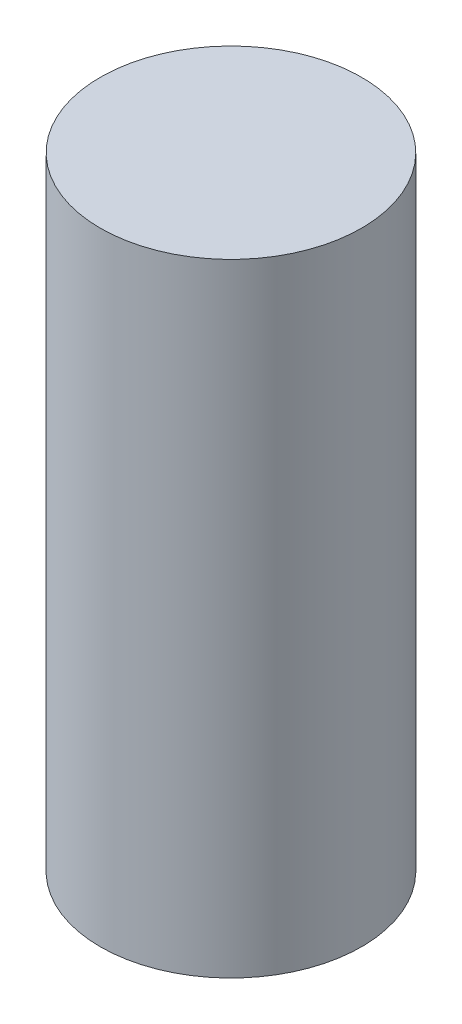
SolidWorks part; units mm, degrees
ref_plane "Plan de face" through (0, 0, 0) normal (0, 0, 1) x (1, 0, 0)
ref_plane "Plan de dessus" through (0, 0, 0) normal (0, 1, 0) x (1, 0, 0)
ref_plane "Plan de droite" through (0, 0, 0) normal (1, 0, 0) x (0, 0, -1)
sketch "Esquisse1" plane through (0, 0, 0) normal (0, 1, 0) x (1, 0, 0)
  circle A0 centre (0, 0) radius 5.25
extrude "Boss.-Extru.1" add sketch "Esquisse1" along normal blind 25
